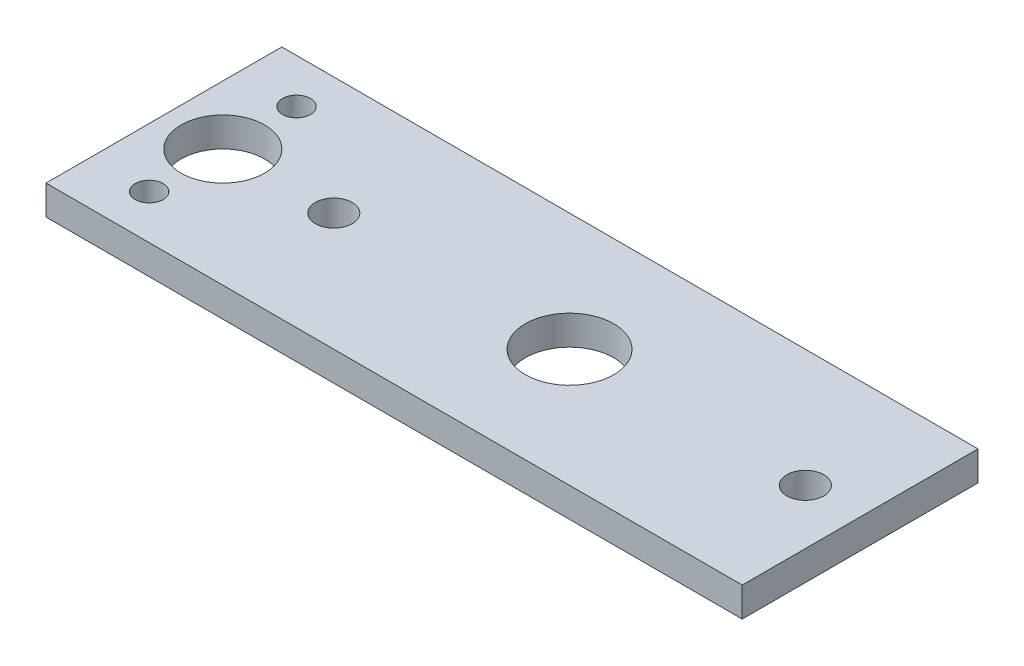
SolidWorks part; units mm, degrees
ref_plane "Front" through (0, 0, 0) normal (0, 0, 1) x (1, 0, 0)
ref_plane "Top" through (0, 0, 0) normal (0, 1, 0) x (1, 0, 0)
ref_plane "Right" through (0, 0, 0) normal (1, 0, 0) x (0, 0, -1)
sketch "Sketch1" plane through (0, 0, 0) normal (0, 1, 0) x (1, 0, 0)
  line L0 (0, 25.4) -> (12.7, 25.4)
  line L1 (0, 0) -> (75, 0)
  line L2 (0, 0) -> (0, 25.4)
  line L3 (0, 25.4) -> (75, 25.4)
  line L4 (75, 0) -> (75, 25.4)
  line L5 (12.7, 25.4) -> (12.7, 0)
  line L6 (12.7, 12.7) -> (43.7, 12.7)
  line L7 (6.35, 25.4) -> (6.35, 20.6375)
  line L8 (6.35, 0) -> (6.35, 4.7625)
  circle A0 centre (43.7, 12.7) radius 4.7625
  circle A1 centre (6.35, 20.6375) radius 1.5
  circle A2 centre (6.35, 4.7625) radius 1.5
  circle A3 centre (6.35, 12.7) radius 4.5
  dimension "D5" = 4.7625
  dimension "D1" = 25.4
  dimension "D2" = 75
  dimension "D3" = 12.7
  dimension "D4" = 31
  dimension "D6" = 4.7625
extrude "Boss-Extrude1" add sketch "Sketch1" along normal blind 3.175
sketch "Sketch2" plane through (0, 0, 0) normal (0, -1, 0) x (-1, 0, 0)
  line L0 (-43.7, 12.7) -> (-18.3, 12.7)
  line L1 (-43.7, 12.7) -> (-69.1, 12.7)
  circle A0 centre (-18.3, 12.7) radius 1.9844
  circle A1 centre (-69.1, 12.7) radius 1.9844
  dimension "D1" = 25.4
extrude "Cut-Extrude1" cut sketch "Sketch2" against normal blind 3.175
